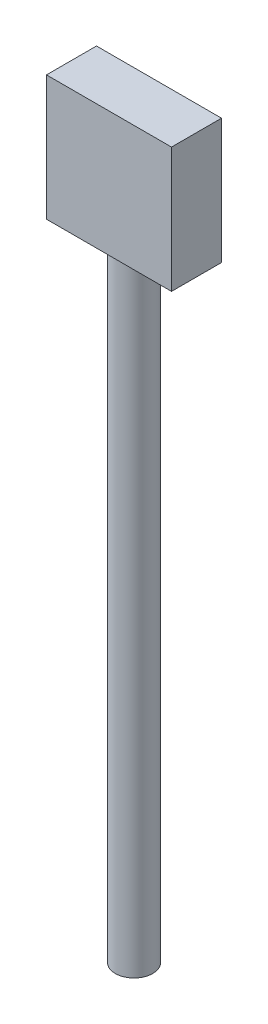
SolidWorks part; units mm, degrees
ref_plane "Front Plane" through (0, 0, 0) normal (0, 0, 1) x (1, 0, 0)
ref_plane "Top Plane" through (0, 0, 0) normal (0, 1, 0) x (1, 0, 0)
ref_plane "Right Plane" through (0, 0, 0) normal (1, 0, 0) x (0, 0, -1)
sketch "Sketch1" plane through (0, 0, 0) normal (0, 1, 0) x (1, 0, 0)
  circle A0 centre (0, 0) radius 1.5
  dimension "D1" = 3
extrude "Boss-Extrude1" add sketch "Sketch1" along normal blind 50
sketch "Sketch2" plane through (0, 50, 0) normal (0, 1, 0) x (1, 0, 0)
  line L0 (-5, 0) -> (-5, -2) construction
  line L1 (0, 0) -> (-5, 0) construction
  line L3 (-5, -2) -> (5, -2)
  line L4 (-5, -2) -> (-5, 2)
  line L5 (-5, 2) -> (5, 2)
  line L6 (5, -2) -> (5, 2)
  dimension "D1" = 5
  dimension "D2" = 2
  dimension "D3" = 4
  dimension "D4" = 10
extrude "Boss-Extrude2" add sketch "Sketch2" along normal blind 10
